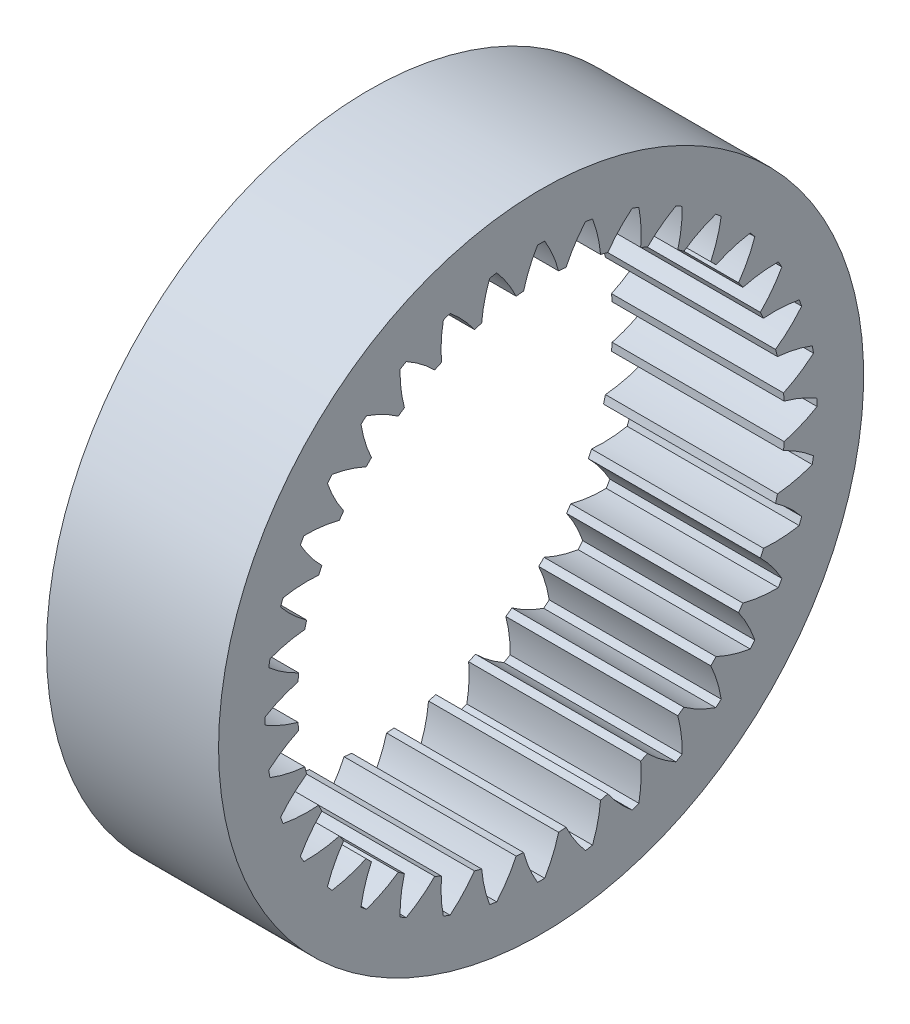
SolidWorks part; units mm, degrees
ref_plane "Plane1" through (0, 0, 0) normal (0, 0, 1) x (1, 0, 0)
ref_plane "Plane2" through (0, 0, 0) normal (0, 1, 0) x (1, 0, 0)
ref_plane "Plane3" through (0, 0, 0) normal (1, 0, 0) x (0, 0, -1)
other "Configuration Table"
sketch "HoldingSke" plane through (0, 0, 0) normal (0, 1, 0) x (1, 0, 0)
  line L0 (0, 0) -> (0.809, -0.5878)
  line L1 (-15, 0) -> (100, 0) construction
  line L2 (0, 0) -> (-2.1039, 2.3779)
  line L3 (0, 0) -> (-11.863, 4.5341)
  line L4 (0, 0) -> (6.9867, 5.0761)
  line L5 (0, 0) -> (-23.7986, -8.8762)
  line L6 (0, 0) -> (-10.5278, -7.1032)
  line L7 (-2.1039, 2.3779) -> (3.3635, 27.1825)
  line L8 (-76.2, 3.3779) -> (-54.61, 3.3779)
  line L9 (-71.009, 38.7566) -> (-53.1078, 45.2721)
  line L10 (-76.2, 71.12) -> (104.1128, 71.12)
  line L11 (0, 0) -> (-12, 0)
  line L12 (-76.2, 101.6) -> (-76.162, 101.6)
  line L13 (24.9733, 27.94) -> (52.9518, 28.4284)
  line L14 (24.9733, 27.94) -> (24.9743, 27.94)
  line L15 (24.9733, 27.94) -> (100.4006, 29.5858)
  circle A0 centre (0, 0) radius 22.5
  circle A1 centre (0, 0) radius 12.7
  circle A2 centre (0, 0) radius 12.7
  dimension "MHD" = 25.4
  dimension "Hub_dia" = 25.4
  dimension "Diameter" = 45
  dimension "Num_teeth" = 36
  dimension "Pitch" = 1
  dimension "Overall_len" = 25.4
  dimension "Show_teeth" = 36
  dimension "Thickness" = 12.7
  dimension "OAL" = 25.4001
  dimension "T_dim" = 21.59
  dimension "Ap" = 20
  dimension "H" = 19.05
  dimension "Pitch_radius" = 180.3128
  dimension "Width" = 12
  dimension "Backlash" = 0.038
  dimension "Addendum_fac" = 1
  dimension "Dedendum_fac" = 1.25
  dimension "Clearance_fac" = 0.25
  dimension "Dedendum_add" = 0.001
  dimension "Module" = 1
sketch "BasProSke" plane through (0, 0, 0) normal (0, 1, 0) x (1, 0, 0)
  line L0 (-10, 0) -> (60, 0) construction
  line L1 (0, 17) -> (0, 22.5)
  line L2 (0, 17) -> (12, 17)
  line L3 (12, 17) -> (12, 22.5)
  line L4 (12, 22.5) -> (0, 22.5)
  dimension "Diameter" = 45
  dimension "Thickness" = 12
  dimension "Inside_diameter" = 34
revolve "Base-Revolve" add sketch "BasProSke" angle 360 about L0
sketch "TooCutSke" plane through (0, 0, 0) normal (1, 0, 0) x (0, 0, -1)
  line L3 (0.8801, 17.9785) -> (0.8801, 53.6633) construction
  line L4 (0, 0) -> (0, 59.563) construction
  line L5 (0, 0) -> (-5.9551, 68.0675) construction
  line L6 (-7.4727, 14.6274) -> (36.372, 18.4633) construction
  circle A0 centre (0, 0) radius 18 construction
  circle A1 centre (0, 0) radius 19.251 construction
  circle A2 centre (0, 0) radius 15.223 construction
  circle A3 centre (0, 0) radius 16.9746 construction
  arc A4 (1.2277, 16.9301) -> (0.2498, 19.2494) centre (-7.4727, 14.6274) ccw
  arc A5 (1.2277, 16.9301) -> (-1.2277, 16.9301) centre (0, 0) ccw
  arc A6 (0.2498, 19.2494) -> (-0.2498, 19.2494) centre (0, 0) ccw
  arc A7 (-0.2498, 19.2494) -> (-1.2277, 16.9301) centre (7.4727, 14.6274) ccw
  dimension "Pitch_dia" = 36
  dimension "Base_dia" = 30.446
  dimension "Root_dia" = 38.502
  dimension "Overcut_dia" = 33.9492
  dimension "Flank_rad" = 9
  dimension "Half_ang" = 5
  dimension "Half_CT" = 0.8801
extrude "ToothCut" cut sketch "TooCutSke" along normal through all
fillet "Breaks" [suppressed] radius 0.1
fillet "RootFillets" [suppressed] radius 0.251
pattern_circular "TeethCuts" count 36 every 10 about axis through (-10, 0, 0) along (1, 0, 0) of "RootFillets", "Breaks", "ToothCut"
equation "' \"Module@HoldingSke\" = 6.35"
equation "' \"Num_teeth@HoldingSke\" = 24"
equation "' \"Ap@HoldingSke\" =  14.5"
equation "' \"Ap@HoldingSke\" = 14.5"
equation "' \"Width@HoldingSke\" = 12"
equation "' \"Diameter@HoldingSke\" = 8 * 25.4"
equation "' \"Show_teeth@HoldingSke\" = 100"
equation "' \"Backlash@HoldingSke\" = 0.009 * 25.4"
equation "' \"Addendum_fac@HoldingSke\" = 1.0"
equation "' \"Dedendum_fac@HoldingSke\" = 1.25"
equation "' \"Dedendum_add@HoldingSke\" = 0.00005 * 25.4"
equation "' \"Clearance_fac@HoldingSke\" = 0.25"
equation "\"Pitch@HoldingSke\" = 1 / \"Module@HoldingSke\" "
equation "\"Overcut_dia@TooCutSke\" = (\"Num_teeth@HoldingSke\" - 2 * \"Addendum_fac@HoldingSke\") / \"Pitch@HoldingSke\" - 0.002 * 25.4"
equation "\"Pitch_dia@TooCutSke\" = \"Num_teeth@HoldingSke\" / \"Pitch@HoldingSke\""
equation "\"Base_dia@TooCutSke\" = \"Num_teeth@HoldingSke\" / \"Pitch@HoldingSke\" * cos((\"Ap@HoldingSke\"  * 3.14159265 / 180)) * 0.90"
equation "\"Root_dia@TooCutSke\" = \"Num_teeth@HoldingSke\"  / \"Pitch@HoldingSke\" + 2 *  \"Dedendum_fac@HoldingSke\"/ \"Pitch@HoldingSke\" + \"Dedendum_add@HoldingSke\" * 2"
equation "\"Half_ang@TooCutSke\" = 180 / \"Num_teeth@HoldingSke\""
equation "\"Half_CT@TooCutSke\" = \"Num_teeth@HoldingSke\" / \"Pitch@HoldingSke\" * sin((3.14159265 / 2 / \"Num_teeth@HoldingSke\")) / 2 + 10 * \"Backlash@HoldingSke\" / 4"
equation "\"Flank_rad@TooCutSke\" = \"Num_teeth@HoldingSke\" / \"Pitch@HoldingSke\" / 4"
equation "\"Radius@RootFillets\"= \"Clearance_fac@HoldingSke\" / \"Pitch@HoldingSke\" + \"Dedendum_add@HoldingSke\""
equation "\"Break_rad@Breaks\" = 0.02 / \"Pitch@HoldingSke\" * 5"
equation "\"Num_teeth@TeethCuts\" = int( \"Show_teeth@HoldingSke\" ) + 1"
equation "\"Num_teeth@TeethCuts\" = ((sgn( \"Num_teeth@TeethCuts\" - \"Num_teeth@HoldingSke\" )-1)*( \"Num_teeth@TeethCuts\" - \"Num_teeth@HoldingSke\" ))/-2+ \"Num_teeth@HoldingSke\""
equation "\"Num_teeth@TeethCuts\" = ((sgn( \"Num_teeth@TeethCuts\" - 2.0)+1)*( \"Num_teeth@TeethCuts\" - 2.0))/2 +2.0"
equation "\"Angle@TeethCuts\" = 360.0 / \"Num_teeth@HoldingSke\""
equation "\"Diameter@BasProSke\" = \"Num_teeth@HoldingSke\"  / \"Pitch@HoldingSke\" + 2 *  \"Dedendum_fac@HoldingSke\"/ \"Pitch@HoldingSke\" + \"Dedendum_add@HoldingSke\" * 2 + 0.002 * 25.4"
equation "\"Diameter@BasProSke\" = ((sgn( \"Diameter@BasProSke\"  - \"Diameter@HoldingSke\" )+1)*( \"Diameter@BasProSke\"  - \"Diameter@HoldingSke\" ))/2 + \"Diameter@HoldingSke\""
equation "\"Inside_diameter@BasProSke\" =  (\"Num_teeth@HoldingSke\" - 2 * \"Addendum_fac@HoldingSke\") / \"Pitch@HoldingSke\" "
equation "\"Thickness@BasProSke\"  = \"Width@HoldingSke\""
